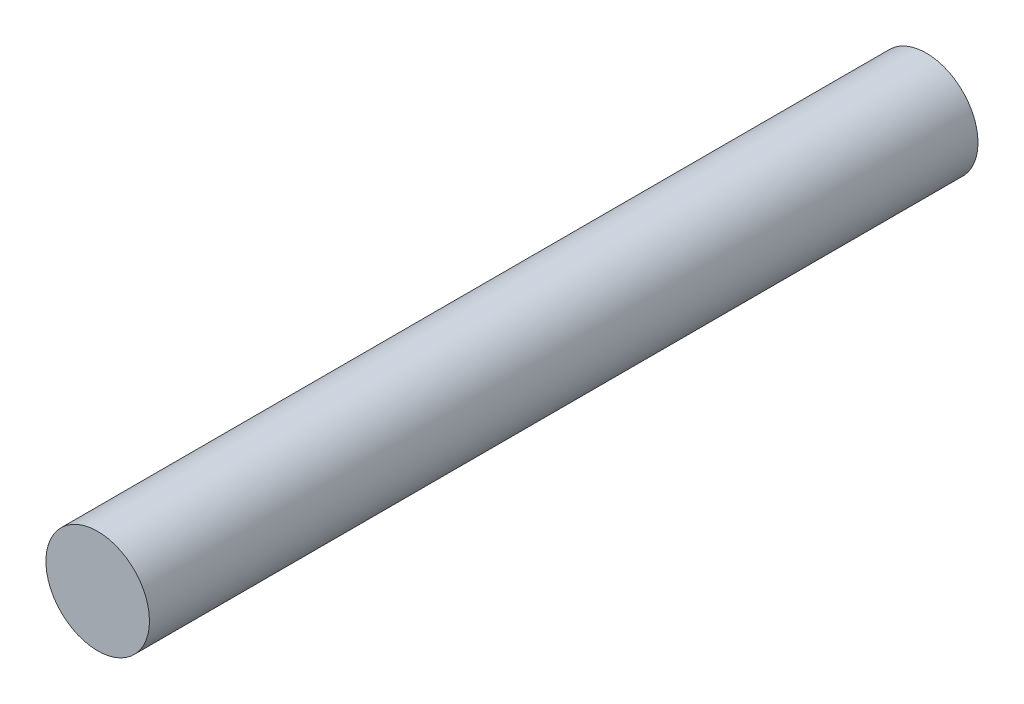
SolidWorks part; units mm, degrees
ref_plane "Front Plane" through (0, 0, 0) normal (0, 0, 1) x (1, 0, 0)
ref_plane "Top Plane" through (0, 0, 0) normal (0, 1, 0) x (1, 0, 0)
ref_plane "Right Plane" through (0, 0, 0) normal (1, 0, 0) x (0, 0, -1)
sketch "Sketch1" plane through (0, 0, 0) normal (0, 0, 1) x (1, 0, 0)
  circle A0 centre (0, 0) radius 1.5875
  dimension "D1" = 3.175
extrude "Boss-Extrude1" add sketch "Sketch1" against normal blind 25.4
